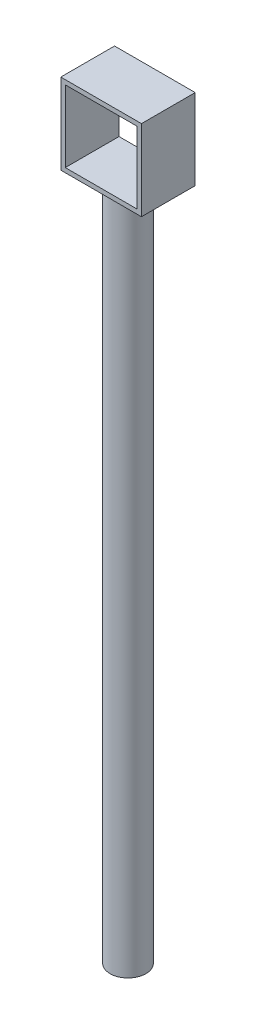
SolidWorks part; units mm, degrees
ref_plane "Front Plane" through (0, 0, 0) normal (0, 0, 1) x (1, 0, 0)
ref_plane "Top Plane" through (0, 0, 0) normal (0, 1, 0) x (1, 0, 0)
ref_plane "Right Plane" through (0, 0, 0) normal (1, 0, 0) x (0, 0, -1)
sketch "Sketch1" plane through (0, 0, 0) normal (0, 0, 1) x (1, 0, 0)
  line L1 (-25.4, -25.4) -> (25.4, -25.4)
  line L2 (-25.4, -25.4) -> (-25.4, 25.4)
  line L3 (-25.4, 25.4) -> (25.4, 25.4)
  line L4 (25.4, -25.4) -> (25.4, 25.4)
  line L5 (-25.4, -25.4) -> (25.4, 25.4) construction
  line L6 (-25.4, 25.4) -> (25.4, -25.4) construction
  line L7 (-28.575, -28.575) -> (28.575, -28.575)
  line L8 (-28.575, -28.575) -> (-28.575, 28.575)
  line L9 (-28.575, 28.575) -> (28.575, 28.575)
  line L10 (28.575, -28.575) -> (28.575, 28.575)
  line L11 (-28.575, -28.575) -> (28.575, 28.575) construction
  line L12 (-28.575, 28.575) -> (28.575, -28.575) construction
  point P0 (0, 0)
  point P7 (0, 0)
  dimension "D1" = 50.8
  dimension "D2" = 50.8
  dimension "D3" = 57.15
  dimension "D4" = 57.15
extrude "Boss-Extrude1" add sketch "Sketch1" along normal blind 38.1
ref_plane "Plane1" through (0, -27.94, 0) normal (0, 1, 0) x (1, 0, 0)
sketch "Sketch4" plane through (0, -27.94, 0) normal (0, 1, 0) x (1, 0, 0)
  circle A0 centre (0, -19.05) radius 12.7
  dimension "D1" = 25.4
  dimension "D2" = 19.05
extrude "Boss-Extrude2" add sketch "Sketch4" against normal blind 482.6
